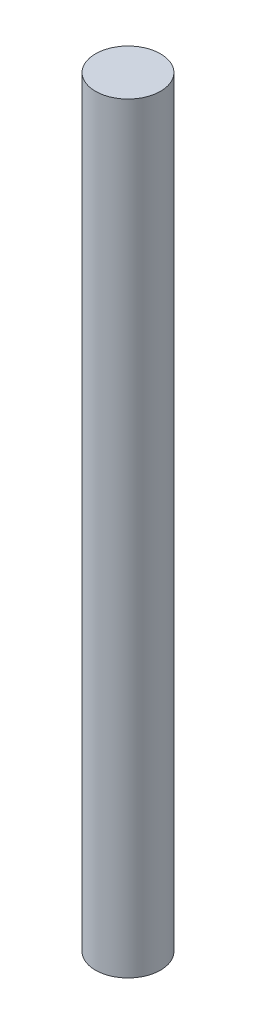
SolidWorks part; units mm, degrees
ref_plane "Front Plane" through (0, 0, 0) normal (0, 0, 1) x (1, 0, 0)
ref_plane "Top Plane" through (0, 0, 0) normal (0, 1, 0) x (1, 0, 0)
ref_plane "Right Plane" through (0, 0, 0) normal (1, 0, 0) x (0, 0, -1)
sketch "Sketch1" plane through (0, 0, 0) normal (0, 1, 0) x (1, 0, 0)
  circle A0 centre (0, 0) radius 0.5207
  dimension "D1" = 1.0414
extrude "Boss-Extrude1" add sketch "Sketch1" along normal mid plane 12.192
